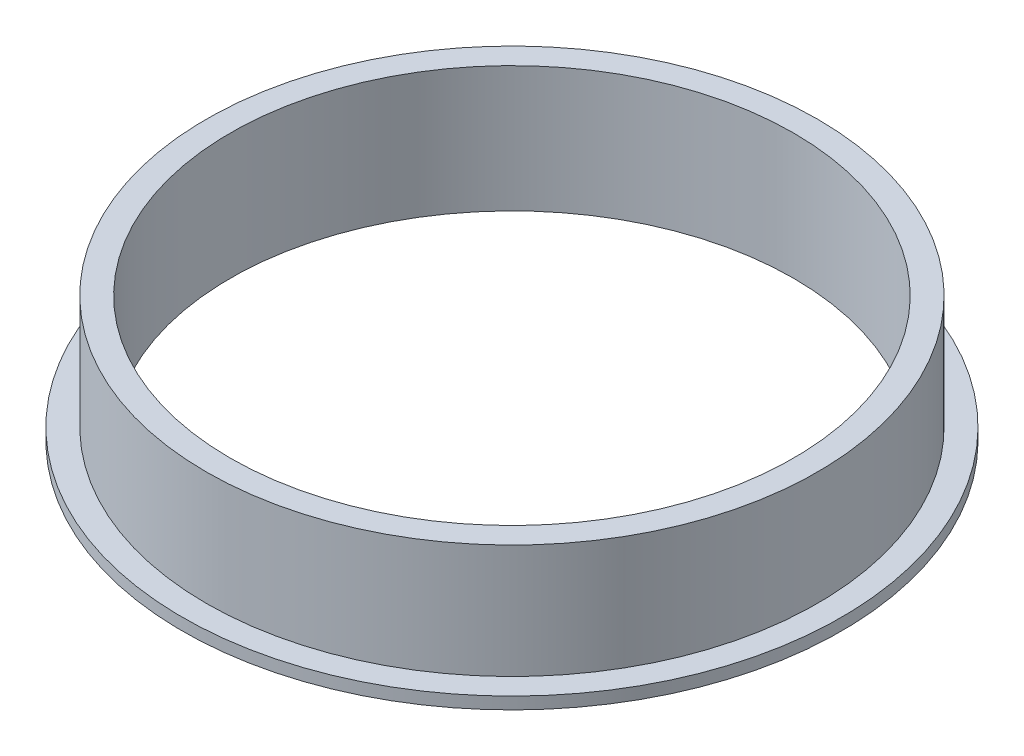
SolidWorks part; units mm, degrees
ref_plane "Front Plane" through (0, 0, 0) normal (0, 0, 1) x (1, 0, 0)
ref_plane "Top Plane" through (0, 0, 0) normal (0, 1, 0) x (1, 0, 0)
ref_plane "Right Plane" through (0, 0, 0) normal (1, 0, 0) x (0, 0, -1)
sketch "Sketch1" plane through (0, 0, 0) normal (0, 1, 0) x (1, 0, 0)
  circle A0 centre (0, 0) radius 23.5
  dimension "D1" = 47
extrude "Extrude-Thin1" add sketch "Sketch1" against normal blind 10.5 thin
sketch "Sketch2" plane through (0, -10.5, 0) normal (0, -1, 0) x (-1, 0, 0)
  circle A0 centre (0, 0) radius 25.5
extrude "Extrude-Thin2" add sketch "Sketch2" against normal blind 1 thin
